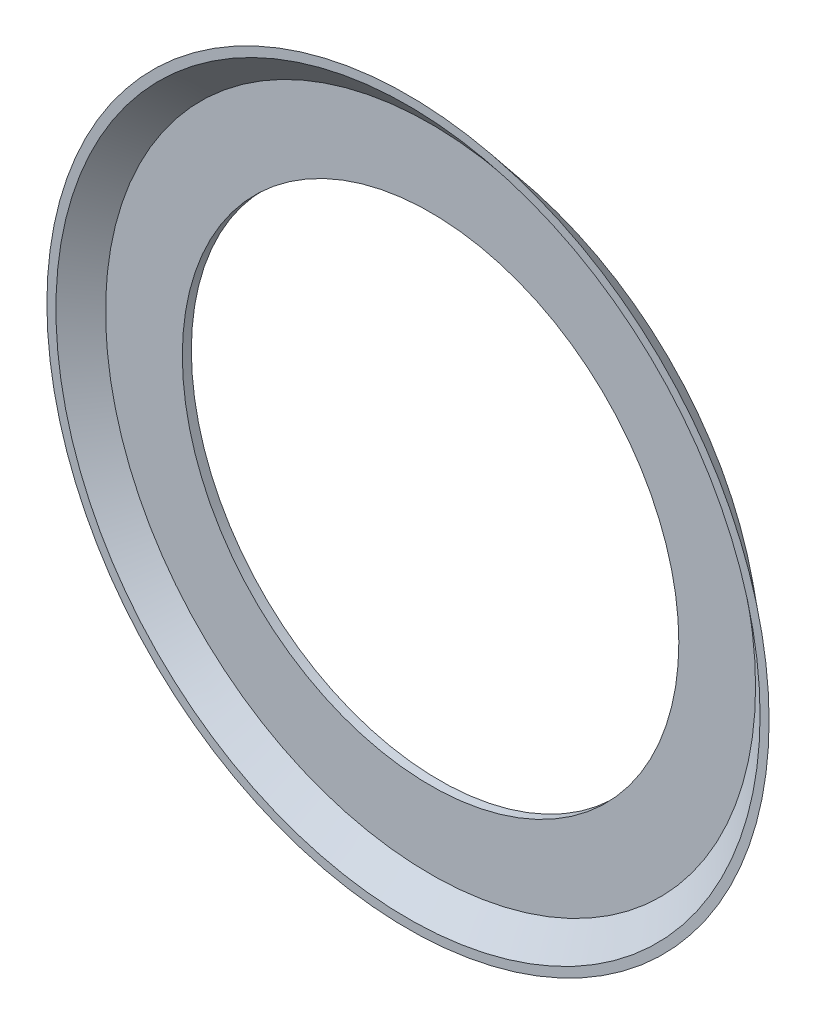
SolidWorks part; units mm, degrees
ref_plane "Front Plane" through (0, 0, 0) normal (0, 0, 1) x (1, 0, 0)
ref_plane "Top Plane" through (0, 0, 0) normal (0, 1, 0) x (1, 0, 0)
ref_plane "Right Plane" through (0, 0, 0) normal (1, 0, 0) x (0, 0, -1)
sketch "Sketch1" plane through (0, 0, 0) normal (1, 0, 0) x (0, 0, -1)
  line L0 (-5, 78) -> (0, 72)
  line L1 (0, 55) -> (0, 72)
  line L2 (-5, 78) -> (-5, 80)
  line L3 (-5, 80) -> (5, 68)
  line L4 (5, 68) -> (5, 66)
  line L5 (2, 55) -> (2, 69.6)
  line L6 (2, 69.6) -> (5, 66)
  line L7 (2, 55) -> (0, 55)
  line L8 (-19.563, 0) -> (30.7138, 0) construction
  dimension "D1" = 2
  dimension "D2" = 2
  dimension "D3" = 80
  dimension "D4" = 68
  dimension "D5" = 10
  dimension "D6" = 55
  dimension "D7" = 3
  dimension "D8" = 2
revolve "Revolve1" add sketch "Sketch1" angle 360 about L8
